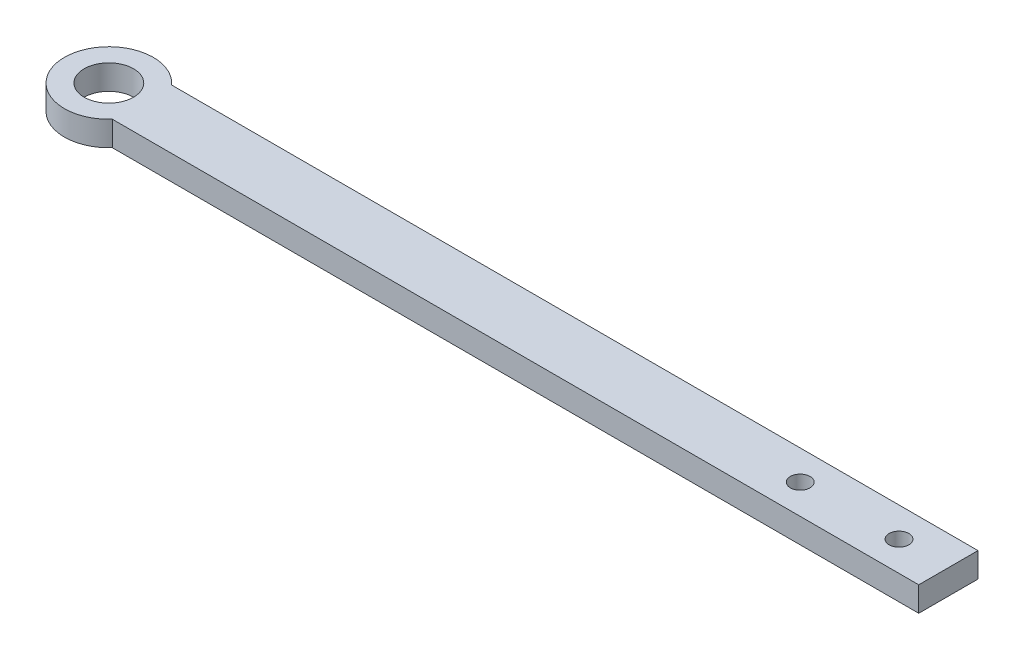
SolidWorks part; units mm, degrees
ref_plane "Front Plane" through (0, 0, 0) normal (0, 0, 1) x (1, 0, 0)
ref_plane "Top Plane" through (0, 0, 0) normal (0, 1, 0) x (1, 0, 0)
ref_plane "Right Plane" through (0, 0, 0) normal (1, 0, 0) x (0, 0, -1)
sketch "Sketch1" plane through (0, 0, 0) normal (0, 1, 0) x (1, 0, 0)
  line L0 (6.7082, 6) -> (170, 6)
  line L1 (170, 6) -> (170, -6)
  line L2 (170, -6) -> (6.7082, -6)
  arc A0 (6.7082, 6) -> (6.7082, -6) centre (0, 0) ccw
  dimension "D1" = 18
  dimension "D2" = 170
  dimension "D3" = 6
extrude "Boss-Extrude1" add sketch "Sketch1" along normal blind 5
sketch "Sketch2" plane through (0, 5, 0) normal (0, 1, 0) x (1, 0, 0)
  line L0 (170, -6) -> (170, 6) construction
  circle A0 centre (0, 0) radius 5
  circle A1 centre (160, 0) radius 2
  circle A2 centre (140, 0) radius 2
  dimension "D1" = 4
  dimension "D4" = 10
  dimension "D2" = 10
  dimension "D3" = 20
extrude "Cut-Extrude1" cut sketch "Sketch2" against normal through all
